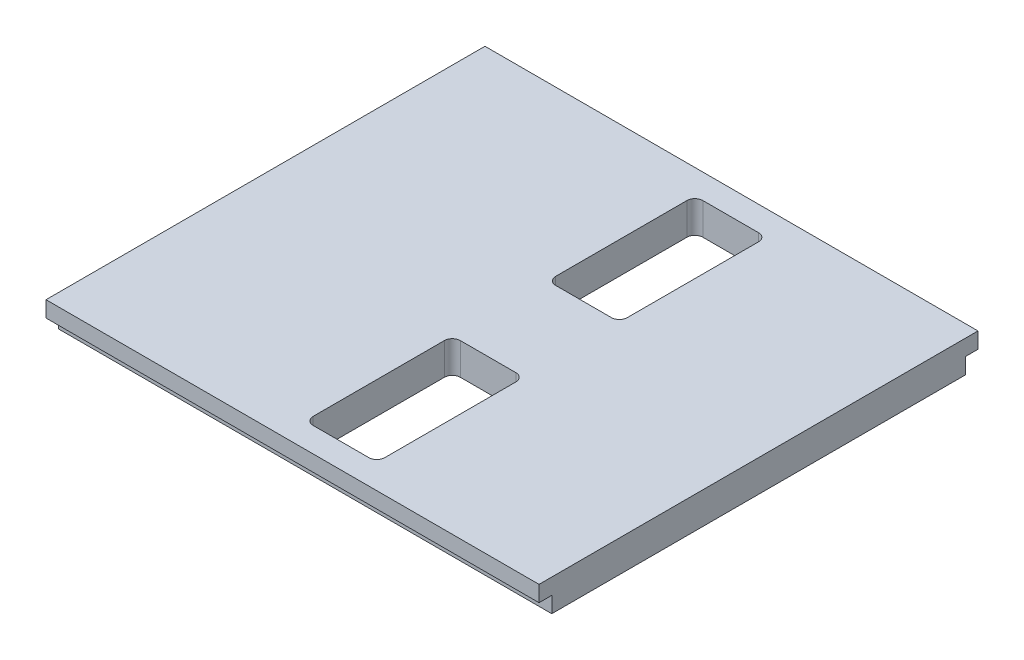
SolidWorks part; units mm, degrees
material "Delrin 2700 NC010, Low Viscosity Acetal Copolymer (SS)"
ref_plane "Front Plane" through (0, 0, 0) normal (0, 0, 1) x (1, 0, 0)
ref_plane "Top Plane" through (0, 0, 0) normal (0, 1, 0) x (1, 0, 0)
ref_plane "Right Plane" through (0, 0, 0) normal (1, 0, 0) x (0, 0, -1)
sketch "Sketch1" plane through (0, 0, 0) normal (1, 0, 0) x (0, 0, -1)
  line L1 (-87.63, -6.35) -> (87.63, -6.35)
  line L2 (-87.63, -6.35) -> (-87.63, 6.35)
  line L3 (-87.63, 6.35) -> (87.63, 6.35)
  line L4 (87.63, -6.35) -> (87.63, 6.35)
  line L5 (-87.63, -6.35) -> (87.63, 6.35) construction
  line L6 (-87.63, 6.35) -> (87.63, -6.35) construction
  point P0 (0, 0)
  dimension "D1" = 175.26
  dimension "D2" = 12.7
extrude "Boss-Extrude1" add sketch "Sketch1" along normal mid plane 196.85
sketch "Sketch2" plane through (98.425, 0, 0) normal (1, 0, 0) x (0, 0, -1)
  line L0 (87.63, 6.35) -> (-87.63, 6.35) construction
  line L1 (-87.63, -6.35) -> (-82.55, -6.35)
  line L2 (-87.63, -6.35) -> (-87.63, 0)
  line L3 (-87.63, 0) -> (-82.55, 0)
  line L4 (-82.55, -6.35) -> (-82.55, 0)
  line L5 (87.63, -6.35) -> (82.55, -6.35)
  line L6 (87.63, -6.35) -> (87.63, 0)
  line L7 (87.63, 0) -> (82.55, 0)
  line L8 (82.55, -6.35) -> (82.55, 0)
  dimension "D1" = 6.35
  dimension "D2" = 165.1
extrude "Cut-Extrude1" cut sketch "Sketch2" against normal through all
sketch "Sketch3" plane through (0, -6.35, 0) normal (0, 1, 0) x (1, 0, 0)
  line L0 (98.425, 87.63) -> (98.425, -87.63) construction
  line L1 (28.448, 11.2395) -> (41.402, 11.2395)
  line L2 (28.448, 4.6355) -> (28.448, -4.6355)
  line L3 (28.448, -11.2395) -> (41.402, -11.2395)
  line L4 (41.402, 4.6355) -> (41.402, -4.6355)
  line L5 (-22.352, 11.2395) -> (-9.398, 11.2395)
  line L6 (-9.398, 4.6355) -> (-9.398, -4.6355)
  line L7 (-22.352, -11.2395) -> (-9.398, -11.2395)
  line L8 (-22.352, 4.6355) -> (-22.352, -4.6355)
  line L17 (28.448, 11.2395) -> (-22.352, 11.2395) construction
  arc A0 (28.448, 11.2395) -> (28.448, 4.6355) centre (28.448, 7.9375) ccw
  arc A1 (28.448, -4.6355) -> (28.448, -11.2395) centre (28.448, -7.9375) ccw
  arc A2 (41.402, -11.2395) -> (41.402, -4.6355) centre (41.402, -7.9375) ccw
  arc A3 (41.402, 4.6355) -> (41.402, 11.2395) centre (41.402, 7.9375) ccw
  arc A4 (-9.398, 4.6355) -> (-9.398, 11.2395) centre (-9.398, 7.9375) ccw
  arc A5 (-9.398, -11.2395) -> (-9.398, -4.6355) centre (-9.398, -7.9375) ccw
  arc A6 (-22.352, -4.6355) -> (-22.352, -11.2395) centre (-22.352, -7.9375) ccw
  arc A7 (-22.352, 11.2395) -> (-22.352, 4.6355) centre (-22.352, 7.9375) ccw
  point P11 (34.925, 11.2395)
  point P15 (41.402, 0)
  point P16 (98.425, 0)
  dimension "D3" = 6.604
  dimension "D1" = 12.954
  dimension "D2" = 22.479
  dimension "D4" = 63.5
  dimension "D8" = 50.8
  dimension "D6" = 2
  dimension "D7" = 1
extrude "Cut-Extrude2" cut sketch "Sketch3" along normal blind 6.35
sketch "Sketch5" plane through (0, 6.35, 0) normal (0, 1, 0) x (1, 0, 0)
  line L0 (98.425, 87.63) -> (98.425, -87.63) construction
  line L1 (23.8125, -77.7875) -> (-4.7625, -77.7875)
  line L2 (23.8125, -77.7875) -> (23.8125, -19.05)
  line L3 (23.8125, -19.05) -> (-4.7625, -19.05)
  line L4 (-4.7625, -77.7875) -> (-4.7625, -19.05)
  line L5 (23.8125, -77.7875) -> (-4.7625, -19.05) construction
  line L6 (23.8125, -19.05) -> (-4.7625, -77.7875) construction
  line L7 (23.8125, 77.7875) -> (-4.7625, 77.7875)
  line L8 (23.8125, 77.7875) -> (23.8125, 19.05)
  line L9 (23.8125, 19.05) -> (-4.7625, 19.05)
  line L10 (-4.7625, 77.7875) -> (-4.7625, 19.05)
  line L11 (23.8125, 77.7875) -> (-4.7625, 19.05) construction
  line L12 (23.8125, 19.05) -> (-4.7625, 77.7875) construction
  point P0 (9.525, -48.4187)
  point P5 (9.525, 48.4187)
  point P12 (98.425, 0)
  point P13 (0, 0)
  dimension "D1" = 28.575
  dimension "D2" = 58.7375
  dimension "D3" = 96.8375
  dimension "D4" = 48.4187
  dimension "D5" = 88.9
extrude "Cut-Extrude4" cut sketch "Sketch5" against normal through all
fillet "Fillet1" radius 3.175 8 edges at (23.8125, 0, -19.05) (23.8125, 0, -77.7875) (-4.7625, 0, -77.7875) (-4.7625, 0, -19.05) (23.8125, 0, 77.7875) (23.8125, 0, 19.05) (-4.7625, 0, 19.05) (-4.7625, 0, 77.7875)
equation "\"D1@Boss-Extrude1\"=7.66629343in "
equation "\"D4@Sketch5\"=\"D3@Sketch5\"/2"
